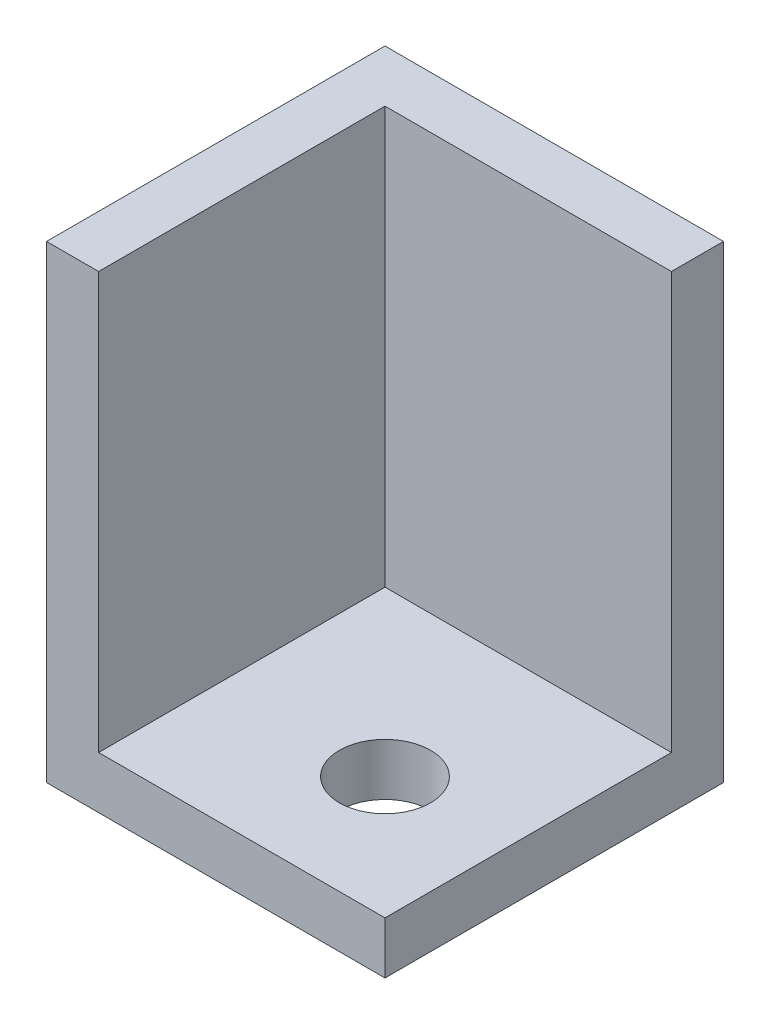
SolidWorks part; units mm, degrees
ref_plane "Front Plane" through (0, 0, 0) normal (0, 0, 1) x (1, 0, 0)
ref_plane "Top Plane" through (0, 0, 0) normal (0, 1, 0) x (1, 0, 0)
ref_plane "Right Plane" through (0, 0, 0) normal (1, 0, 0) x (0, 0, -1)
sketch "Sketch1" plane through (0, 0, 0) normal (0, 1, 0) x (1, 0, 0)
  line L0 (0, 15.4918) -> (0, -27.6639) construction
  line L1 (-27.2213, 0) -> (42.0492, 0) construction
  line L3 (6.5, -6.5) -> (-6.5, -6.5)
  line L4 (6.5, -6.5) -> (6.5, 6.5)
  line L5 (6.5, 6.5) -> (-6.5, 6.5)
  line L6 (-6.5, -6.5) -> (-6.5, 6.5)
  line L7 (6.5, -6.5) -> (-6.5, 6.5) construction
  line L8 (6.5, 6.5) -> (-6.5, -6.5) construction
  point P5 (0, 0)
  dimension "D1" = 13
  dimension "D2" = 13
extrude "Boss-Extrude1" add sketch "Sketch1" along normal blind 2
sketch "Sketch2" plane through (0, 2, 0) normal (0, 1, 0) x (1, 0, 0)
  line L0 (0.5, 10.6578) -> (0.5, -14.7204) construction
  line L1 (-6.5, -6.5) -> (6.5, -6.5)
  line L2 (-6.5, -6.5) -> (-6.5, 6.5)
  line L3 (-6.5, 6.5) -> (6.5, 6.5)
  line L4 (6.5, -6.5) -> (6.5, 6.5)
  line L5 (-11.8782, -0.5) -> (19.1349, -0.5) construction
  line L6 (-4.5, -6.5) -> (-4.5, 4.5)
  line L7 (-4.5, 4.5) -> (6.5, 4.5)
  circle A0 centre (0.5, -0.5) radius 3.5
  line M9 (-6.5, 6.5) -> (-6.5, -6.5)
  line M10 (-6.5, -6.5) -> (6.5, -6.5)
  line M12 (6.5, 6.5) -> (-6.5, 6.5)
  dimension "D3" = 2
  dimension "D5" = 7
  dimension "D1" = 6
  dimension "D2" = 6
  dimension "D4" = 2
extrude "Boss-Extrude2" add sketch "Sketch2" along normal blind 16 contours L6 L7 L4 M12 M9 M10
sketch "Sketch3" plane through (0, 2, 0) normal (0, 1, 0) x (1, 0, 0)
  line L0 (-11.8916, -1.8) -> (15.4916, -1.8) construction
  line L1 (1.8, 4.4198) -> (1.8, -14.0564) construction
  line L4 (6.5, 6.5) -> (-6.5, 6.5) construction
  circle A0 centre (1.8, -1.8) radius 1.75
  point P6 (0, 0)
  dimension "D3" = 3.5
  dimension "D1" = 8.3
  dimension "D2" = 8.3
extrude "Cut-Extrude1" cut sketch "Sketch3" against normal blind 20
sketch "Sketch4" plane through (0, 2, 0) normal (0, 1, 0) x (1, 0, 0)
  line L0 (6.5, -6.5) -> (-6.5, 6.5) construction
